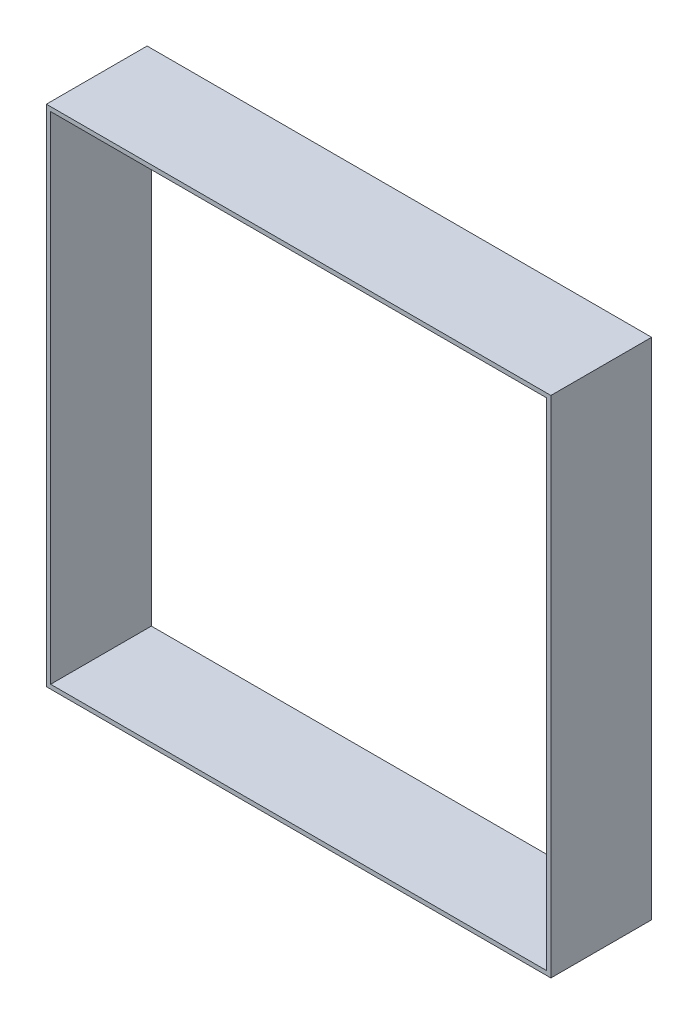
SolidWorks part; units mm, degrees
material "Beech"
ref_plane "Front Plane" through (0, 0, 0) normal (0, 0, 1) x (1, 0, 0)
ref_plane "Top Plane" through (0, 0, 0) normal (0, 1, 0) x (1, 0, 0)
ref_plane "Right Plane" through (0, 0, 0) normal (1, 0, 0) x (0, 0, -1)
sketch "Sketch1" plane through (0, 0, 0) normal (0, 0, 1) x (1, 0, 0)
  line L0 (-320, -320) -> (320, -320)
  line L1 (-320, -320) -> (-320, 320)
  line L2 (-320, 320) -> (320, 320)
  line L3 (320, -320) -> (320, 320)
  line L4 (-320, -320) -> (320, 320) construction
  line L5 (-320, 320) -> (320, -320) construction
  line L6 (-325.5, -325.5) -> (325.5, -325.5)
  line L7 (-325.5, -325.5) -> (-325.5, 325.5)
  line L8 (-325.5, 325.5) -> (325.5, 325.5)
  line L9 (325.5, -325.5) -> (325.5, 325.5)
  line L10 (-325.5, -325.5) -> (325.5, 325.5) construction
  line L11 (-325.5, 325.5) -> (325.5, -325.5) construction
  point P0 (0, 0)
  point P5 (0, 0)
  point P6 (0, 0)
  dimension "D1" = 640
  dimension "D2" = 5.5
extrude "Boss-Extrude1" add sketch "Sketch1" along normal blind 130
